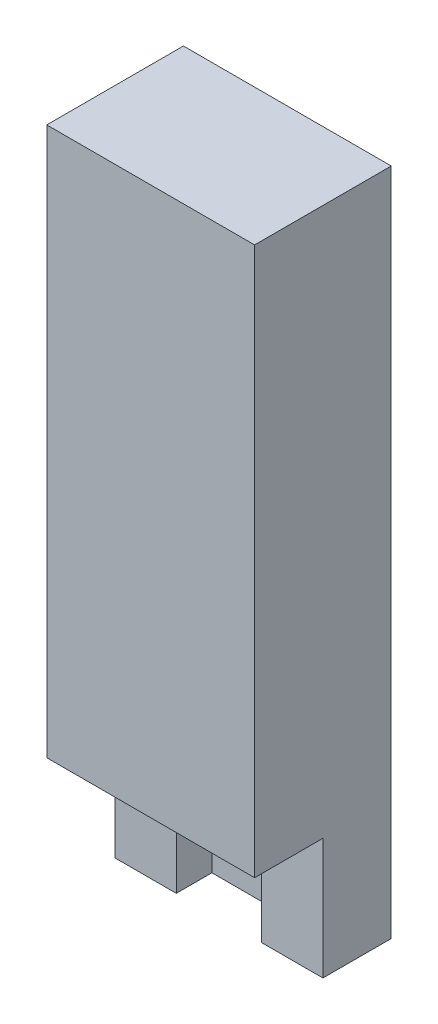
SolidWorks part; units mm, degrees
ref_plane "前视基准面" through (0, 0, 0) normal (0, 0, 1) x (1, 0, 0)
ref_plane "上视基准面" through (0, 0, 0) normal (0, 1, 0) x (1, 0, 0)
ref_plane "右视基准面" through (0, 0, 0) normal (1, 0, 0) x (0, 0, -1)
other "Configuration Table"
sketch "草图1" plane through (0, 0, 0) normal (0, 0, 1) x (1, 0, 0)
  line L1 (-7.3, 0) -> (7.3, 0) construction
  line L2 (-7.3, 0) -> (-7.3, 38.5)
  line L3 (-7.3, 38.5) -> (7.3, 38.5)
  line L4 (7.3, 0) -> (7.3, 38.5)
  line L5 (-7.3, 0) -> (7.3, 0) construction
  line L6 (-7.3, 0) -> (-7.3, -8.5)
  line L7 (-7.3, -8.5) -> (7.3, -8.5)
  line L8 (7.3, 0) -> (7.3, -8.5)
  point P4 (0, 0)
  point P10 (0, 0)
  dimension "D1" = 38.5
  dimension "D2" = 14.6
  dimension "D3" = 8.5
extrude "凸台-拉伸1" add sketch "草图1" along normal blind 9.6 contours L4 L3 L2 L6 L7 L8
sketch "草图2" plane through (0, 0, 9.6) normal (0, 0, 1) x (1, 0, 0)
  line L0 (7.3, 38.5) -> (7.3, -8.5) construction
  line L1 (-7.3, -8.5) -> (7.3, -8.5)
  line L2 (-7.3, -8.5) -> (-7.3, 0)
  line L3 (-7.3, 0) -> (7.3, 0)
  line L4 (7.3, -8.5) -> (7.3, 0)
  dimension "D1" = 8.5
extrude "切除-拉伸1" cut sketch "草图2" against normal blind 4.8
sketch "草图3" plane through (0, 0, 4.8) normal (0, 0, 1) x (1, 0, 0)
  line L0 (-7.3, -8.5) -> (7.3, -8.5) construction
  line L1 (-3, -8.5) -> (3, -8.5)
  line L2 (-3, -8.5) -> (-3, 0)
  line L3 (-3, 0) -> (3, 0)
  line L4 (3, -8.5) -> (3, 0)
  line L5 (7.3, 0) -> (-7.3, 0) construction
  point P8 (0, 0)
  dimension "D1" = 6
extrude "切除-拉伸2" cut sketch "草图3" against normal blind 2.5
